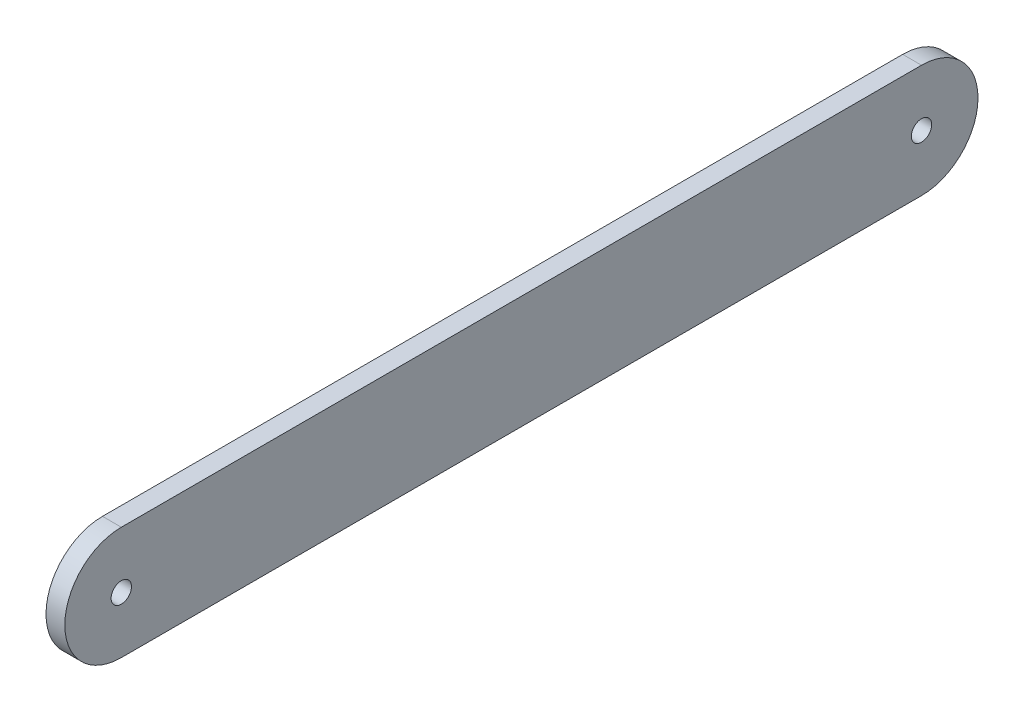
SolidWorks part; units mm, degrees
ref_plane "Front Plane" through (0, 0, 0) normal (0, 0, 1) x (1, 0, 0)
ref_plane "Top Plane" through (0, 0, 0) normal (0, 1, 0) x (1, 0, 0)
ref_plane "Right Plane" through (0, 0, 0) normal (1, 0, 0) x (0, 0, -1)
sketch "Sketch1" plane through (0, 0, 0) normal (1, 0, 0) x (0, 0, -1)
  line L1 (-106.25, -15) -> (106.25, -15)
  line L3 (-106.25, 15) -> (106.25, 15)
  line L5 (-106.25, -15) -> (106.25, 15) construction
  line L6 (-106.25, 15) -> (106.25, -15) construction
  arc A0 (-106.25, 15) -> (-106.25, -15) centre (-106.25, 0) ccw
  arc A1 (106.25, -15) -> (106.25, 15) centre (106.25, 0) ccw
  circle A2 centre (-106.25, 0) radius 2.7
  circle A3 centre (106.25, 0) radius 2.7
  point P0 (0, 0)
  dimension "D1" = 15
  dimension "D3" = 15
  dimension "D4" = 5.4
  dimension "D5" = 5.4
  dimension "D2" = 212.5
  dimension "D6" = 30
extrude "Boss-Extrude1" add sketch "Sketch1" along normal blind 5
